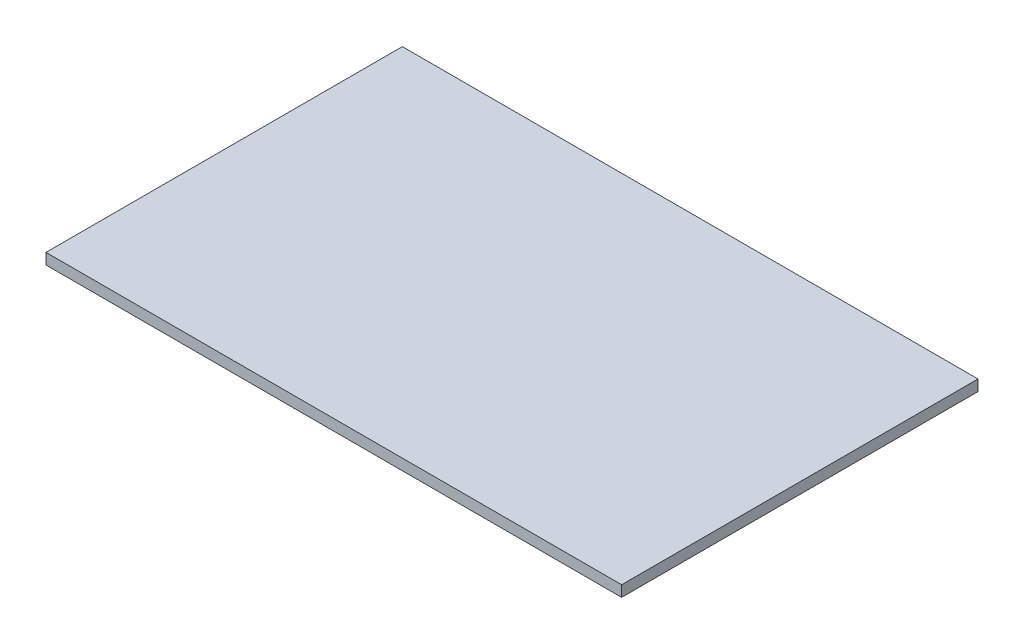
SolidWorks part; units mm, degrees
ref_plane "Ebene vorne" through (0, 0, 0) normal (0, 0, 1) x (1, 0, 0)
ref_plane "Ebene oben" through (0, 0, 0) normal (0, 1, 0) x (1, 0, 0)
ref_plane "Ebene rechts" through (0, 0, 0) normal (1, 0, 0) x (0, 0, -1)
sketch "Skizze3" plane through (0, 0, 0) normal (0, 1, 0) x (1, 0, 0)
  line L0 (0, 0) -> (105, 0)
  line L1 (-55, 0) -> (55, 0) construction
  line L2 (105, 0) -> (105, 65)
  line L3 (105, 65) -> (0, 65)
  line L4 (0, -55) -> (0, 55) construction
  line L5 (0, 65) -> (0, 0)
  dimension "D1" = 105
  dimension "D2" = 65
extrude "Aufsatz-Linear austragen1" add sketch "Skizze3" along normal blind 2
